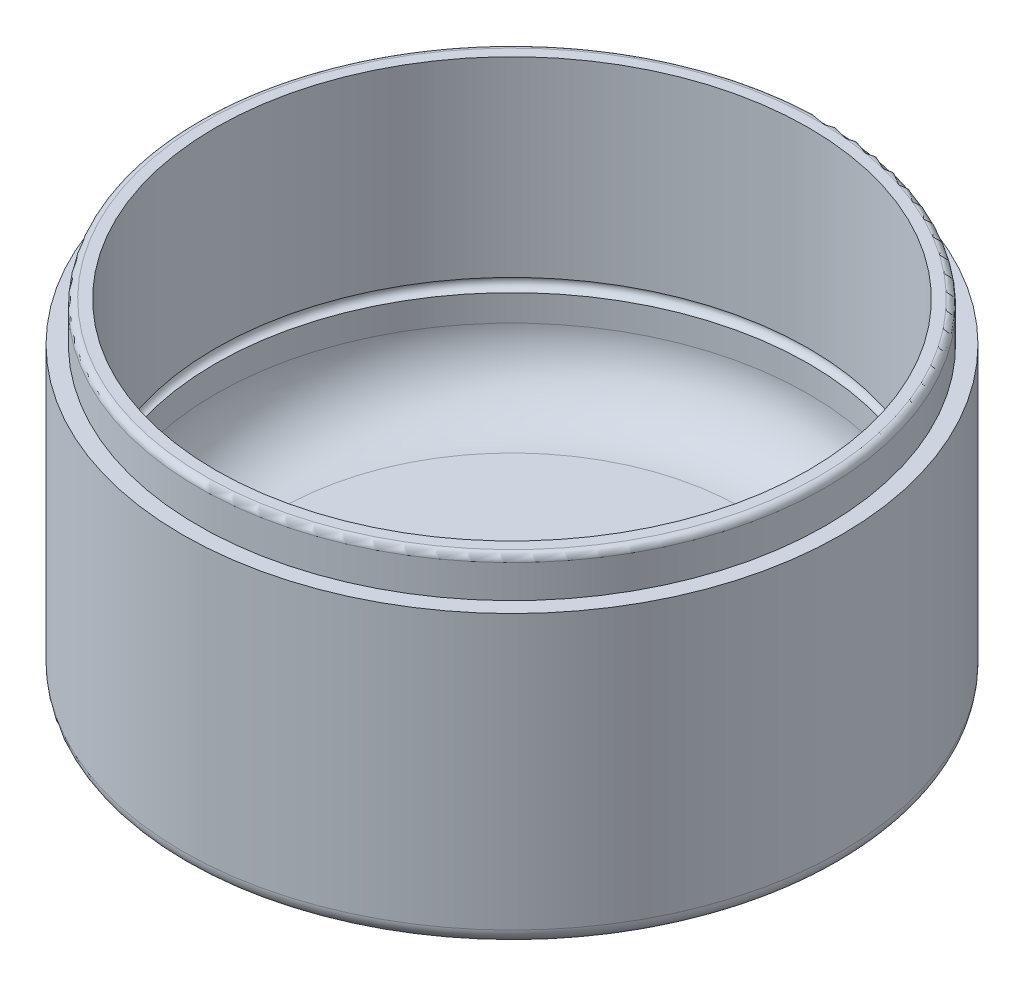
SolidWorks part; units mm, degrees
ref_plane "Front (XY)" through (0, 0, 0) normal (0, 0, 1) x (1, 0, 0)
ref_plane "Top (XZ)" through (0, 0, 0) normal (0, 1, 0) x (1, 0, 0)
ref_plane "Right (YZ)" through (0, 0, 0) normal (1, 0, 0) x (0, 0, -1)
sketch "Sketch1" plane through (0, 0, 0) normal (0, 1, 0) x (1, 0, 0)
  circle A0 centre (0, 0) radius 50
  dimension "D1" = 100
extrude "Boss-Extrude1" add sketch "Sketch1" against normal blind 50
shell "Shell2" thickness 5
sketch "Sketch2" plane through (0, 0, 0) normal (0, 1, 0) x (1, 0, 0)
  line L0 (0, 0) -> (50, 0) construction
  circle A2 centre (0, 0) radius 50 construction
sketch "Sketch3" plane through (0, 0, 0) normal (0, 0, 1) x (1, 0, 0)
  line L0 (50, 0) -> (47.6, 0)
  line L1 (0, 0) -> (50, 0) construction
  line L2 (47.6, 0) -> (47.6, -6)
  line L3 (47.6, -6) -> (50, -6)
  line L4 (50, -50) -> (50, 0) construction
  line L5 (50, -6) -> (50, 0)
  dimension "D1" = 6
  dimension "D2" = 2.4
sketch "Sketch4" plane through (0, 0, 0) normal (0, 1, 0) x (1, 0, 0)
  circle A2 centre (0, 0) radius 47.6
  circle A3 centre (0, 0) radius 47.6
  dimension "D1" = 2.4
sweep "Cut-Sweep1" cut profiles "Sketch3" path "Sketch4"
fillet "Fillet1" radius 1 1 edges at (47.6, 0, 0)
fillet "Fillet2" radius 10 1 edges at (0, -45, 45)
fillet "Fillet3" radius 2.4 1 edges at (0, -50, 50)
ref_plane "Plane1" through (0, -30, 0) normal (0, 1, 0) x (1, 0, 0)
sketch "Sketch5" plane through (0, -30, 0) normal (0, 1, 0) x (1, 0, 0)
  circle A0 centre (0, 0) radius 45
sketch "Sketch6" plane through (0, 0, 0) normal (0, 0, 1) x (1, 0, 0)
  line L0 (0, -30) -> (45, -30) construction
  line L1 (45, -30) -> (-45, -30) construction
  circle A0 centre (45, -30) radius 1
  dimension "D1" = 2
sweep "Cut-Sweep2" cut profiles "Sketch6" path "Sketch5"
